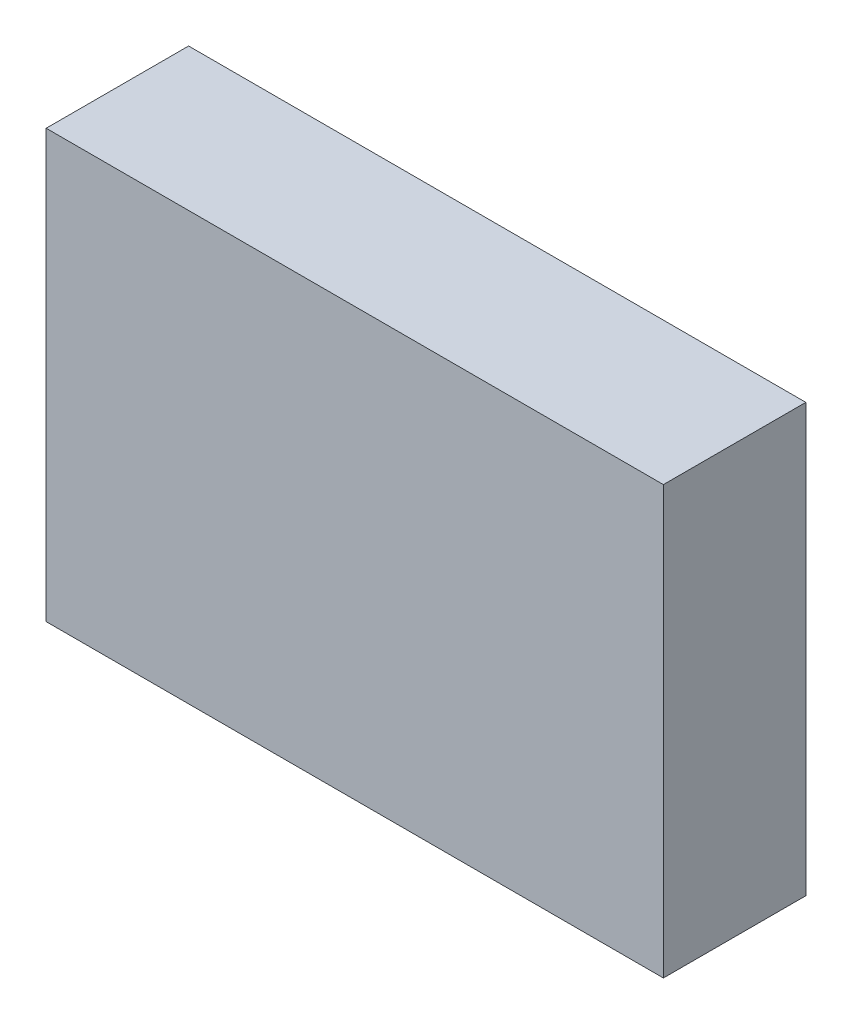
SolidWorks part; units mm, degrees
material "Low Carbon Steel"
ref_plane "Front Plane" through (0, 0, 0) normal (0, 0, 1) x (1, 0, 0)
ref_plane "Top Plane" through (0, 0, 0) normal (0, 1, 0) x (1, 0, 0)
ref_plane "Right Plane" through (0, 0, 0) normal (1, 0, 0) x (0, 0, -1)
sketch "Sketch1" plane through (0, 0, 0) normal (0, 0, 1) x (1, 0, 0)
  line L0 (-82.55, -57.15) -> (82.55, 57.15) construction
  line L1 (-82.55, 57.15) -> (82.55, 57.15)
  line L2 (-82.55, 57.15) -> (-82.55, -57.15)
  line L3 (-82.55, -57.15) -> (82.55, -57.15)
  line L4 (82.55, 57.15) -> (82.55, -57.15)
  dimension "D1" = 114.3
  dimension "D2" = 165.1
extrude "Boss-Extrude1" add sketch "Sketch1" along normal blind 38.1
other "Freeze***"
